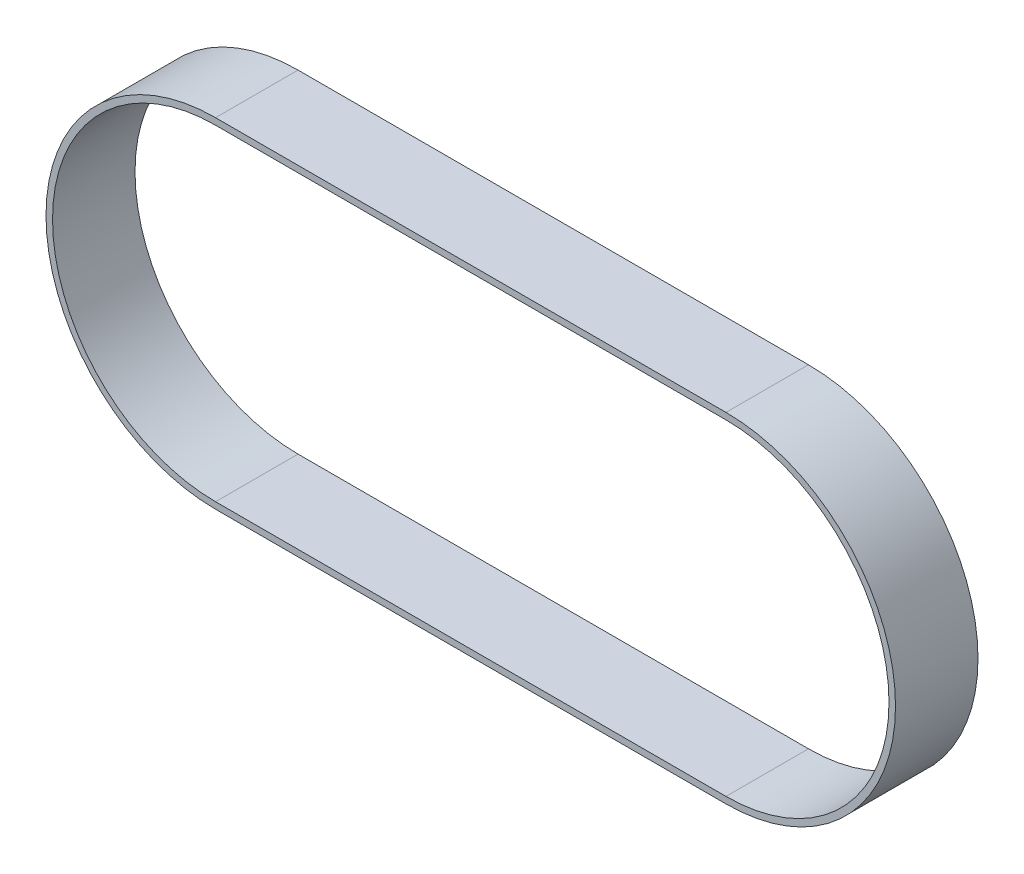
SolidWorks part; units mm, degrees
ref_plane "Front Plane" through (0, 0, 0) normal (0, 0, 1) x (1, 0, 0)
ref_plane "Top Plane" through (0, 0, 0) normal (0, 1, 0) x (1, 0, 0)
ref_plane "Right Plane" through (0, 0, 0) normal (1, 0, 0) x (0, 0, -1)
sketch "Sketch2" plane through (0, 0, 0) normal (0, 0, 1) x (1, 0, 0)
  line L0 (-168.8078, 0) -> (-12.2678, 0) construction
  line L1 (-168.8078, 50) -> (-12.2678, 50)
  line L2 (-168.8078, -50) -> (-12.2678, -50)
  line L3 (-168.8078, 52) -> (-12.2678, 52)
  line L4 (-168.8078, -52) -> (-12.2678, -52)
  arc A0 (-168.8078, 50) -> (-168.8078, -50) centre (-168.8078, 0) ccw
  arc A1 (-12.2678, -50) -> (-12.2678, 50) centre (-12.2678, 0) ccw
  arc A2 (-12.2678, -52) -> (-12.2678, 52) centre (-12.2678, 0) ccw
  arc A3 (-168.8078, 52) -> (-168.8078, -52) centre (-168.8078, 0) ccw
  point P3 (-90.5378, 0)
  dimension "D1" = 50
  dimension "D2" = 156.54
  dimension "D3" = 2
extrude "Boss-Extrude1" add sketch "Sketch2" along normal mid plane 25.3
